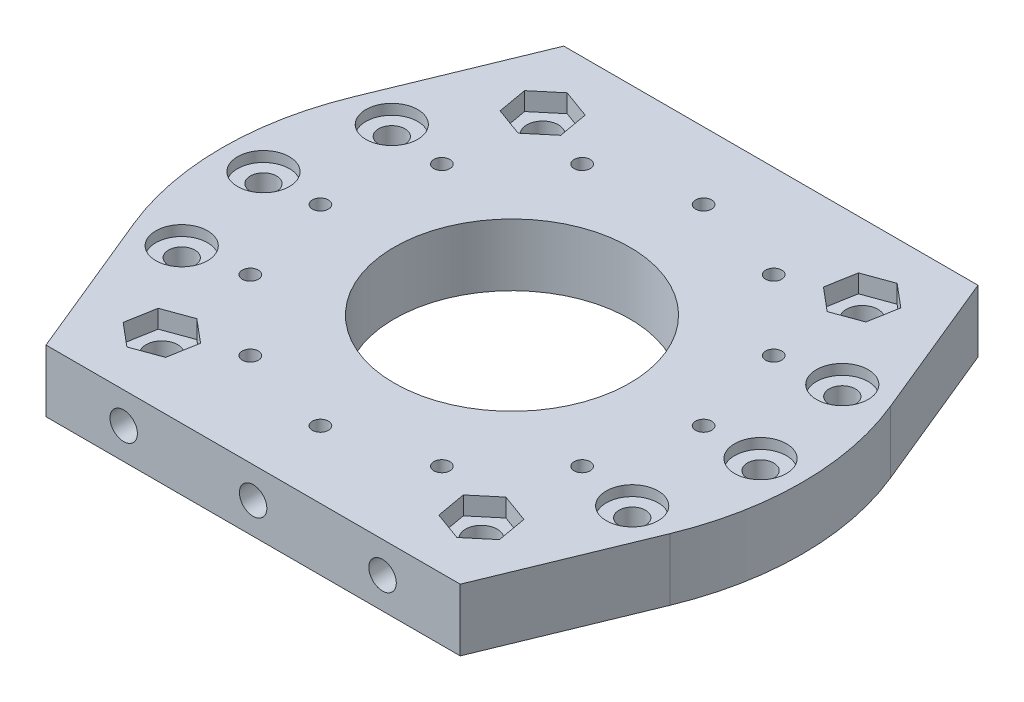
SolidWorks part; units mm, degrees
material "6061 Alloy"
ref_plane "Front Plane" through (0, 0, 0) normal (0, 0, 1) x (1, 0, 0)
ref_plane "Top Plane" through (0, 0, 0) normal (0, 1, 0) x (1, 0, 0)
ref_plane "Right Plane" through (0, 0, 0) normal (1, 0, 0) x (0, 0, -1)
sketch "Sketch1" plane through (0, 0, 0) normal (0, 1, 0) x (1, 0, 0)
  line L5 (0, 0) -> (0, -45) construction
  line L8 (0, 45) -> (0, 0) construction
  line L11 (5, 0) -> (-5, 0) construction
  line L13 (-49.0833, 0) -> (49.0833, 0) construction
  line L17 (40, 50) -> (-40, 50)
  line L18 (-40, -50) -> (40, -50)
  line L19 (-51.7989, 21.2809) -> (-40, 50)
  line L20 (-51.7989, -21.2809) -> (-40, -50)
  line L21 (51.7989, -21.2809) -> (40, -50)
  line L22 (51.7989, 21.2809) -> (40, 50)
  arc A9 (-51.7989, 21.2809) -> (-51.7989, -21.2809) centre (0, 0) ccw
  circle A10 centre (0, 0) radius 42.5 construction
  arc A11 (51.7989, 21.2809) -> (51.7989, -21.2809) centre (0, 0) cw
  point P6 (0, -50)
  point P11 (0, 50)
  dimension "D1" = 56
  dimension "D3" = 50
  dimension "D4" = 40
  dimension "D2" = 85
  dimension "D6" = 5
  dimension "D5" = 50
extrude "КрышкаRa_Harm" add sketch "Sketch1" along normal mid plane 12
sketch "Sketch2" plane through (0, 6, 0) normal (0, 1, 0) x (1, 0, 0)
  circle A0 centre (0, 0) radius 22.75
  dimension "D1" = 45.5
extrude "Cut-Extrude1" cut sketch "Sketch2" against normal up to surface (12 mm away) up to face at (0, -6, 0)
sketch "Sketch3" plane through (0, 6, 0) normal (0, 1, 0) x (1, 0, 0)
  line L0 (0, 37) -> (0, 0) construction
  circle A0 centre (0, 0) radius 37 construction
  circle A1 centre (0, 37) radius 1.55
  circle A2 centre (18.5, 32.0429) radius 1.55
  circle A3 centre (32.0429, 18.5) radius 1.55
  circle A4 centre (37, 0) radius 1.55
  circle A5 centre (32.0429, -18.5) radius 1.55
  circle A6 centre (18.5, -32.0429) radius 1.55
  circle A7 centre (0, -37) radius 1.55
  circle A8 centre (-18.5, -32.0429) radius 1.55
  circle A9 centre (-32.0429, -18.5) radius 1.55
  circle A10 centre (-37, 0) radius 1.55
  circle A11 centre (-32.0429, 18.5) radius 1.55
  circle A12 centre (-18.5, 32.0429) radius 1.55
  point P21 (0, 0)
  dimension "D1" = 37
  dimension "D2" = 3.1
  dimension "D3" = 12
extrude "M4_through" cut sketch "Sketch3" against normal up to surface (12 mm away) up to face at (0, -6, 22.75)
sketch "Sketch5" plane through (0, 0, 50) normal (0, 0, 1) x (1, 0, 0)
  line L0 (0, -5) -> (0, 5) construction
  line L2 (0, 0) -> (-25, 0) construction
  circle A0 centre (-25, 0) radius 2.65
  circle A1 centre (25, 0) radius 2.65
  circle A2 centre (0, 0) radius 2.65
  dimension "D1" = 5.3
  dimension "D2" = 25
extrude "M5x8_DRILL2" cut sketch "Sketch5" against normal blind 8
sketch "Эскиз8" plane through (0, 0, -50) normal (0, 0, -1) x (-1, 0, 0)
  circle A0 centre (-25, 0) radius 2.65
  circle A1 centre (0, 0) radius 2.65
  circle A2 centre (25, 0) radius 2.65
  dimension "D1" = 5.3
extrude "Вырез-Вытянуть6" cut sketch "Эскиз8" against normal blind 8
sketch "Эскиз9" plane through (0, -6, 0) normal (0, -1, 0) x (1, 0, 0)
  line L0 (-43.5028, 20.2857) -> (0, 0) construction
  line L1 (0, 0) -> (-48, 0) construction
  line L2 (-43.5028, -20.2857) -> (0, 0) construction
  line L3 (0, 0) -> (0, 21.1309) construction
  line L4 (-30.8538, 36.7701) -> (0, 0) construction
  circle A0 centre (-48, 0) radius 2.55
  circle A1 centre (-43.5028, -20.2857) radius 2.55
  circle A4 centre (-43.5028, 20.2857) radius 2.55
  circle A11 centre (-30.8538, 36.7701) radius 3.05
  circle A12 centre (-30.8538, -36.7701) radius 3.05
  circle A13 centre (30.8538, -36.7701) radius 3.05
  circle A14 centre (30.8538, 36.7701) radius 3.05
  circle A15 centre (43.5028, 20.2857) radius 2.55
  circle A16 centre (43.5028, -20.2857) radius 2.55
  circle A17 centre (48, 0) radius 2.55
  point P12 (0, 0)
  point P15 (0, 0)
  dimension "D2" = 5.1
  dimension "D7" = 6.1
  dimension "D1" = 48
  dimension "D5" = 25
  dimension "D6" = 25
  dimension "D8" = 25
  dimension "D3" = 2
  dimension "D4" = 2
extrude "Вырез-Вытянуть8" cut sketch "Эскиз9" against normal up to surface (12 mm away) up to face at (0, 6, -35.45)
sketch "Эскиз10" plane through (0, 6, 0) normal (0, 1, 0) x (1, 0, 0)
  line L0 (-30.8538, 36.7701) -> (0, 0) construction
  line L1 (-26.3868, 40.5184) -> (-31.8664, 42.5128)
  line L2 (-31.8664, 42.5128) -> (-36.3334, 38.7645)
  line L3 (-36.3334, 38.7645) -> (-35.3208, 33.0219)
  line L4 (-35.3208, 33.0219) -> (-29.8412, 31.0275)
  line L5 (-29.8412, 31.0275) -> (-25.3742, 34.7757)
  line L6 (-25.3742, 34.7757) -> (-26.3868, 40.5184)
  line L7 (25.3742, 34.7757) -> (29.8412, 31.0275)
  line L8 (29.8412, 31.0275) -> (35.3208, 33.0219)
  line L9 (35.3208, 33.0219) -> (36.3334, 38.7645)
  line L10 (36.3334, 38.7645) -> (31.8664, 42.5128)
  line L11 (31.8664, 42.5128) -> (26.3868, 40.5184)
  line L12 (26.3868, 40.5184) -> (25.3742, 34.7757)
  line L13 (-25.3742, -34.7757) -> (-29.8412, -31.0275)
  line L14 (-29.8412, -31.0275) -> (-35.3208, -33.0219)
  line L15 (-35.3208, -33.0219) -> (-36.3334, -38.7645)
  line L16 (-36.3334, -38.7645) -> (-31.8664, -42.5128)
  line L17 (-31.8664, -42.5128) -> (-26.3868, -40.5184)
  line L18 (-26.3868, -40.5184) -> (-25.3742, -34.7757)
  line L19 (35.3208, -33.0219) -> (29.8412, -31.0275)
  line L20 (29.8412, -31.0275) -> (25.3742, -34.7757)
  line L21 (25.3742, -34.7757) -> (26.3868, -40.5184)
  line L22 (26.3868, -40.5184) -> (31.8664, -42.5128)
  line L23 (31.8664, -42.5128) -> (36.3334, -38.7645)
  line L24 (36.3334, -38.7645) -> (35.3208, -33.0219)
  line L25 (0, 0) -> (30.8538, 36.7701) construction
  line L26 (-30.8538, -36.7701) -> (0, 0) construction
  line L27 (0, 0) -> (30.8538, -36.7701) construction
  circle A0 centre (-30.8538, 36.7701) radius 5.05 construction
  circle A1 centre (30.8538, 36.7701) radius 5.05 construction
  circle A2 centre (-30.8538, -36.7701) radius 5.05 construction
  circle A3 centre (30.8538, -36.7701) radius 5.05 construction
  dimension "D1" = 10.1
extrude "Вырез-Вытянуть9" cut sketch "Эскиз10" against normal blind 3.5
sketch "Эскиз11" plane through (0, -6, 0) normal (0, -1, 0) x (1, 0, 0)
  line L0 (21.45, 33.7461) -> (18.5, 35.4493)
  line L1 (1.7032, 39.95) -> (-1.7032, 39.95)
  line L2 (-1.7032, 39.95) -> (-3.4064, 37)
  line L3 (-3.4064, 37) -> (-1.7032, 34.05)
  line L4 (-1.7032, 34.05) -> (1.7032, 34.05)
  line L5 (1.7032, 34.05) -> (3.4064, 37)
  line L6 (3.4064, 37) -> (1.7032, 39.95)
  line L7 (18.5, 35.4493) -> (15.55, 33.7461)
  line L8 (15.55, 33.7461) -> (15.55, 30.3398)
  line L9 (15.55, 30.3398) -> (18.5, 28.6366)
  line L10 (18.5, 28.6366) -> (21.45, 30.3398)
  line L11 (21.45, 30.3398) -> (21.45, 33.7461)
  line L12 (35.4493, 18.5) -> (33.7461, 21.45)
  line L13 (33.7461, 21.45) -> (30.3398, 21.45)
  line L14 (30.3398, 21.45) -> (28.6366, 18.5)
  line L15 (28.6366, 18.5) -> (30.3398, 15.55)
  line L16 (30.3398, 15.55) -> (33.7461, 15.55)
  line L17 (33.7461, 15.55) -> (35.4493, 18.5)
  line L18 (39.95, -1.7032) -> (39.95, 1.7032)
  line L19 (39.95, 1.7032) -> (37, 3.4064)
  line L20 (37, 3.4064) -> (34.05, 1.7032)
  line L21 (34.05, 1.7032) -> (34.05, -1.7032)
  line L22 (34.05, -1.7032) -> (37, -3.4064)
  line L23 (37, -3.4064) -> (39.95, -1.7032)
  line L24 (33.7461, -21.45) -> (35.4493, -18.5)
  line L25 (35.4493, -18.5) -> (33.7461, -15.55)
  line L26 (33.7461, -15.55) -> (30.3398, -15.55)
  line L27 (30.3398, -15.55) -> (28.6366, -18.5)
  line L28 (28.6366, -18.5) -> (30.3398, -21.45)
  line L29 (30.3398, -21.45) -> (33.7461, -21.45)
  line L30 (18.5, -35.4493) -> (21.45, -33.7461)
  line L31 (21.45, -33.7461) -> (21.45, -30.3398)
  line L32 (21.45, -30.3398) -> (18.5, -28.6366)
  line L33 (18.5, -28.6366) -> (15.55, -30.3398)
  line L34 (15.55, -30.3398) -> (15.55, -33.7461)
  line L35 (15.55, -33.7461) -> (18.5, -35.4493)
  line L36 (-1.7032, -39.95) -> (1.7032, -39.95)
  line L37 (1.7032, -39.95) -> (3.4064, -37)
  line L38 (3.4064, -37) -> (1.7032, -34.05)
  line L39 (1.7032, -34.05) -> (-1.7032, -34.05)
  line L40 (-1.7032, -34.05) -> (-3.4064, -37)
  line L41 (-3.4064, -37) -> (-1.7032, -39.95)
  line L42 (-21.45, -33.7461) -> (-18.5, -35.4493)
  line L43 (-18.5, -35.4493) -> (-15.55, -33.7461)
  line L44 (-15.55, -33.7461) -> (-15.55, -30.3398)
  line L45 (-15.55, -30.3398) -> (-18.5, -28.6366)
  line L46 (-18.5, -28.6366) -> (-21.45, -30.3398)
  line L47 (-21.45, -30.3398) -> (-21.45, -33.7461)
  line L48 (-35.4493, -18.5) -> (-33.7461, -21.45)
  line L49 (-33.7461, -21.45) -> (-30.3398, -21.45)
  line L50 (-30.3398, -21.45) -> (-28.6366, -18.5)
  line L51 (-28.6366, -18.5) -> (-30.3398, -15.55)
  line L52 (-30.3398, -15.55) -> (-33.7461, -15.55)
  line L53 (-33.7461, -15.55) -> (-35.4493, -18.5)
  line L54 (-39.95, 1.7032) -> (-39.95, -1.7032)
  line L55 (-39.95, -1.7032) -> (-37, -3.4064)
  line L56 (-37, -3.4064) -> (-34.05, -1.7032)
  line L57 (-34.05, -1.7032) -> (-34.05, 1.7032)
  line L58 (-34.05, 1.7032) -> (-37, 3.4064)
  line L59 (-37, 3.4064) -> (-39.95, 1.7032)
  line L60 (-33.7461, 21.45) -> (-35.4493, 18.5)
  line L61 (-35.4493, 18.5) -> (-33.7461, 15.55)
  line L62 (-33.7461, 15.55) -> (-30.3398, 15.55)
  line L63 (-30.3398, 15.55) -> (-28.6366, 18.5)
  line L64 (-28.6366, 18.5) -> (-30.3398, 21.45)
  line L65 (-30.3398, 21.45) -> (-33.7461, 21.45)
  line L66 (-18.5, 35.4493) -> (-21.45, 33.7461)
  line L67 (-21.45, 33.7461) -> (-21.45, 30.3398)
  line L68 (-21.45, 30.3398) -> (-18.5, 28.6366)
  line L69 (-18.5, 28.6366) -> (-15.55, 30.3398)
  line L70 (-15.55, 30.3398) -> (-15.55, 33.7461)
  line L71 (-15.55, 33.7461) -> (-18.5, 35.4493)
  circle A0 centre (0, 37) radius 2.95 construction
  circle A1 centre (18.5, 32.0429) radius 2.95 construction
  circle A2 centre (32.0429, 18.5) radius 2.95 construction
  circle A3 centre (37, 0) radius 2.95 construction
  circle A4 centre (32.0429, -18.5) radius 2.95 construction
  circle A5 centre (18.5, -32.0429) radius 2.95 construction
  circle A6 centre (0, -37) radius 2.95 construction
  circle A7 centre (-18.5, -32.0429) radius 2.95 construction
  circle A8 centre (-32.0429, -18.5) radius 2.95 construction
  circle A9 centre (-37, 0) radius 2.95 construction
  circle A10 centre (-32.0429, 18.5) radius 2.95 construction
  circle A11 centre (-18.5, 32.0429) radius 2.95 construction
  point P99 (0, 0)
  dimension "D1" = 5.9
  dimension "D2" = 12
extrude "Вырез-Вытянуть10" cut sketch "Эскиз11" against normal blind 3
sketch "Эскиз12" plane through (0, 6, 0) normal (0, 1, 0) x (1, 0, 0)
  circle A0 centre (-43.5028, 20.2857) radius 5
  circle A1 centre (-48, 0) radius 5
  circle A2 centre (-43.5028, -20.2857) radius 5
  circle A3 centre (43.5028, -20.2857) radius 5
  circle A4 centre (48, 0) radius 5
  circle A5 centre (43.5028, 20.2857) radius 5
  dimension "D1" = 10
extrude "Вырез-Вытянуть11" cut sketch "Эскиз12" against normal blind 2
sketch "Эскиз13" plane through (0, -6, 0) normal (0, -1, 0) x (1, 0, 0)
  circle A0 centre (0, 0) radius 39.75
  circle A1 centre (0, 0) radius 33.75
  dimension "D1" = 79.5
  dimension "D2" = 6
extrude "Бобышка-Вытянуть1" add sketch "Эскиз13" along normal blind 4 separate body
sketch "Эскиз14" plane through (0, -10, 0) normal (0, -1, 0) x (1, 0, 0)
  circle A0 centre (0, 37) radius 4
  circle A1 centre (18.5, 32.0429) radius 4
  circle A2 centre (32.0429, 18.5) radius 4
  circle A3 centre (37, 0) radius 4
  circle A4 centre (32.0429, -18.5) radius 4
  circle A5 centre (18.5, -32.0429) radius 4
  circle A6 centre (0, -37) radius 4
  circle A7 centre (-18.5, -32.0429) radius 4
  circle A8 centre (-32.0429, -18.5) radius 4
  circle A9 centre (-37, 0) radius 4
  circle A10 centre (-32.0429, 18.5) radius 4
  circle A11 centre (-18.5, 32.0429) radius 4
  point P27 (0, 0)
  dimension "D1" = 8
  dimension "D2" = 12
extrude "Вырез-Вытянуть12" cut sketch "Эскиз14" against normal blind 4
